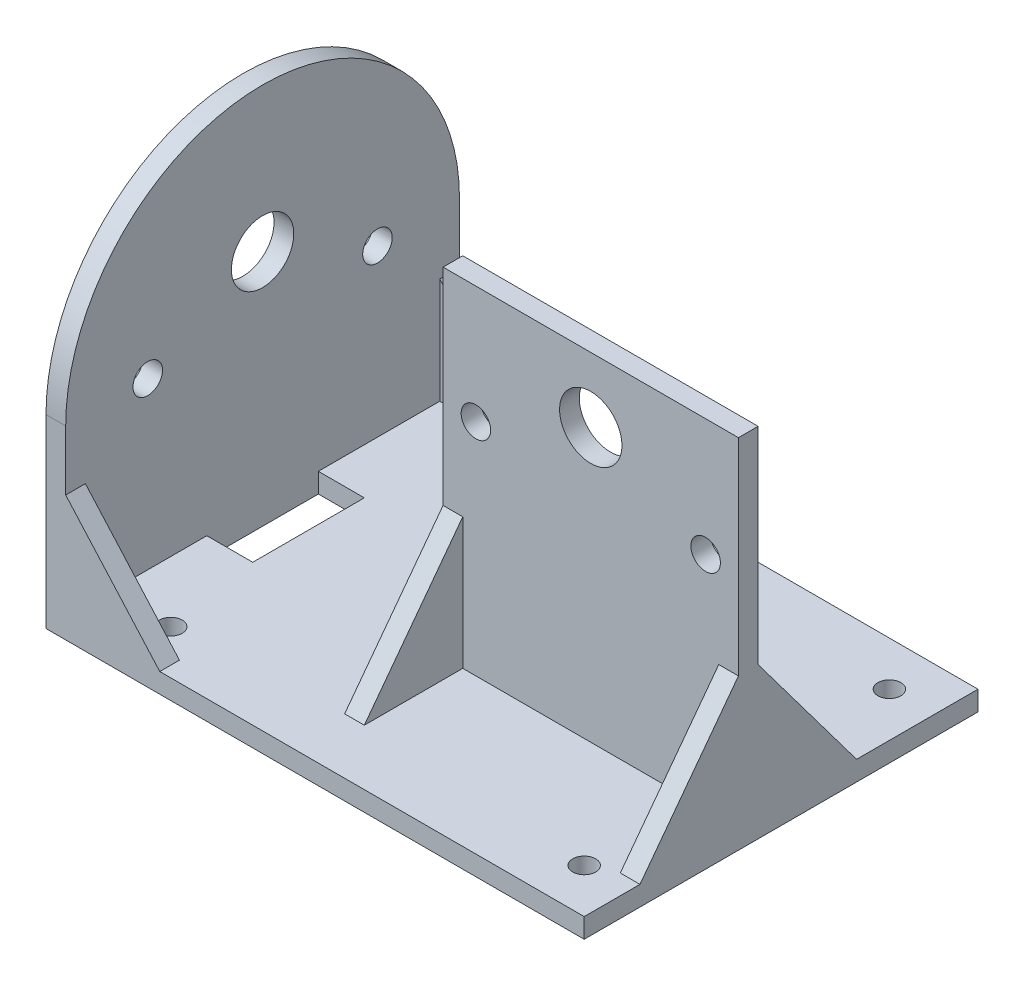
SolidWorks part; units mm, degrees
ref_plane "Front Plane" through (0, 0, 0) normal (0, 0, 1) x (1, 0, 0)
ref_plane "Top Plane" through (0, 0, 0) normal (0, 1, 0) x (1, 0, 0)
ref_plane "Right Plane" through (0, 0, 0) normal (1, 0, 0) x (0, 0, -1)
sketch "Sketch1" plane through (0, 0, 0) normal (0, 1, 0) x (1, 0, 0)
  line L0 (41, -30) -> (-41, -30)
  line L1 (41, -30) -> (41, 30)
  line L2 (-41, -30) -> (-41, 30)
  line L3 (41, 30) -> (-41, 30)
  line L4 (41, -30) -> (-41, 30) construction
  line L5 (-41, -30) -> (41, 30) construction
  point P1 (0, 0)
  dimension "D1" = 60
  dimension "D2" = 82
extrude "Boss-Extrude1" add sketch "Sketch1" along normal blind 3 contours L3 L2 L0 L1
sketch "Sketch2" plane through (0, 0, 30) normal (0, 0, 1) x (1, 0, 0)
  line L0 (-41, 0) -> (-41, 22.5)
  line L1 (-41, 22.5) -> (-21, 0)
  line L2 (-21, 0) -> (-41, 0)
  dimension "D1" = 20
extrude "Boss-Extrude2" add sketch "Sketch2" against normal blind 3
ref_plane "Plane1" through (0, 0, 0) normal (0, 0, 1) x (1, 0, 0)
mirror "Mirror1" about plane through (0, 0, 0) normal (0, 0, 1) of "Boss-Extrude2"
sketch "Sketch3" plane through (-41, 0, 0) normal (-1, 0, 0) x (0, 0, 1)
  line L6 (17.5, 28.2369) -> (-17.5, 28.2369) construction
  line L7 (-30, 0) -> (30, 0)
  line L8 (0, 28.2369) -> (0, 36.2369) construction
  line L9 (-30, 0) -> (-30, 28.2369)
  line L11 (30, 28.2369) -> (30, 0)
  circle A1 centre (-17.5, 28.2369) radius 2.25
  circle A2 centre (17.5, 28.2369) radius 2.25
  circle A3 centre (0, 36.2369) radius 4.75
  arc A6 (30, 28.2369) -> (-30, 28.2369) centre (0, 28.2369) ccw
  point P9 (0, 28.2369)
  dimension "D1" = 9.5
  dimension "D2" = 4.5
  dimension "D3" = 35
extrude "Boss-Extrude3" add sketch "Sketch3" against normal blind 3
sketch "Sketch4" plane through (0, 3, 0) normal (0, 1, 0) x (1, 0, 0)
  line L1 (-38, -8.5) -> (-31, -8.5)
  line L2 (-38, 8.5) -> (-31, 8.5)
  line L3 (-31, -8.5) -> (-31, 8.5)
  line L4 (-38, -27) -> (-38, -30) construction
  line L7 (-38, 8.5) -> (-38, -8.5)
  point P1 (-19.5, 0)
  point P5 (-31, 0)
  dimension "D1" = 17
  dimension "D2" = 7
extrude "Cut-Extrude1" cut sketch "Sketch4" against normal blind 3
sketch "Sketch5" plane through (0, 0, 30) normal (0, 0, 1) x (1, 0, 0)
  line L1 (-4, 0) -> (41, 0)
  line L2 (-4, 0) -> (-4, 54.4417)
  line L3 (-4, 54.4417) -> (41, 54.4417)
  line L4 (41, 0) -> (41, 54.4417)
  dimension "D1" = 45
extrude "Boss-Extrude4" add sketch "Sketch5" against normal blind 3 from offset 23.5 offset against normal yes
sketch "Sketch6" plane through (0, 0, 6.5) normal (0, 0, 1) x (1, 0, 0)
  line L0 (36, 36.5364) -> (1, 36.5364) construction
  line L1 (41, 54.4417) -> (-4, 54.4417) construction
  line L2 (18.5, 36.5364) -> (18.5, 44.5364) construction
  circle A0 centre (1, 36.5364) radius 2.25
  circle A1 centre (36, 36.5364) radius 2.25
  circle A2 centre (18.5, 44.5364) radius 4.75
  point P3 (18.5, 36.5364)
  point P8 (18.5, 54.4417)
  dimension "D1" = 9.5
  dimension "D2" = 4.5
  dimension "D3" = 4.5
  dimension "D4" = 35
  dimension "D5" = 8
extrude "Cut-Extrude2" cut sketch "Sketch6" against normal blind 3 contours A2 | A0 | A1
sketch "Sketch7" plane through (41, 0, 0) normal (1, 0, 0) x (0, 0, -1)
  line L0 (-30, 3) -> (-6.5, 3) construction
  line L1 (-3.5, 3) -> (30, 3) construction
  line L2 (-3.5, 3) -> (-3.5, 54.4417) construction
  line L3 (-6.5, 3) -> (-6.5, 54.4417) construction
  line L4 (-21.5, 3) -> (-6.5, 3)
  line L5 (-3.5, 3) -> (11.5, 3)
  line L6 (-3.5, 3) -> (-3.5, 23)
  line L7 (-6.5, 3) -> (-6.5, 23)
  line L8 (11.5, 3) -> (-3.5, 23)
  line L9 (-6.5, 23) -> (-21.5, 3)
  dimension "D2" = 15
  dimension "D3" = 20
extrude "Boss-Extrude5" add sketch "Sketch7" against normal blind 3
ref_plane "Plane2" through (18.5, 0, 0) normal (-1, 0, 0) x (0, 0, 1)
mirror "Mirror2" about plane through (18.5, 0, 0) normal (-1, 0, 0) of "Boss-Extrude5"
sketch "Sketch8" plane through (0, 0, 0) normal (0, -1, 0) x (1, 0, 0)
  line L0 (41, 30) -> (41, -30) construction
  line L1 (-28.75, -23.25) -> (34.25, -23.25) construction
  line L2 (-28.75, -23.25) -> (-28.75, 23.25) construction
  line L3 (-28.75, 23.25) -> (34.25, 23.25) construction
  line L12 (34.25, -23.25) -> (34.25, 23.25) construction
  circle A0 centre (-28.75, 23.25) radius 1.75
  circle A1 centre (34.25, 23.25) radius 1.75
  circle A2 centre (34.25, -23.25) radius 1.75
  circle A3 centre (-28.75, -23.25) radius 1.75
  point P3 (41, 0)
  point P5 (34.25, 0)
  dimension "D4" = 3.5
  dimension "D2" = 46.5
  dimension "D3" = 63
  dimension "D1" = 6.75
extrude "Cut-Extrude3" cut sketch "Sketch8" against normal blind 3
